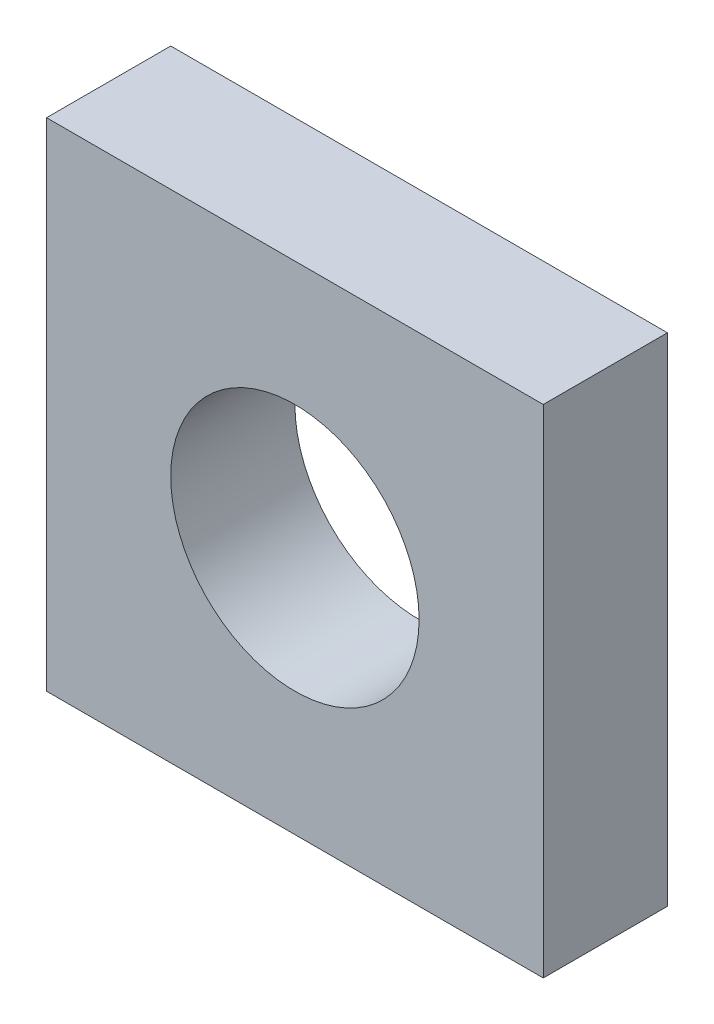
SolidWorks part; units mm, degrees
ref_plane "정면" through (0, 0, 0) normal (0, 0, 1) x (1, 0, 0)
ref_plane "윗면" through (0, 0, 0) normal (0, 1, 0) x (1, 0, 0)
ref_plane "우측면" through (0, 0, 0) normal (1, 0, 0) x (0, 0, -1)
sketch "스케치1" plane through (0, 0, 0) normal (0, 0, 1) x (1, 0, 0)
  line L1 (-20, -20) -> (20, -20)
  line L2 (-20, -20) -> (-20, 20)
  line L3 (-20, 20) -> (20, 20)
  line L4 (20, -20) -> (20, 20)
  line L5 (-20, -20) -> (20, 20) construction
  line L6 (-20, 20) -> (20, -20) construction
  circle A0 centre (0, 0) radius 10
  point P0 (0, 0)
extrude "보스-돌출1" add sketch "스케치1" along normal blind 10
